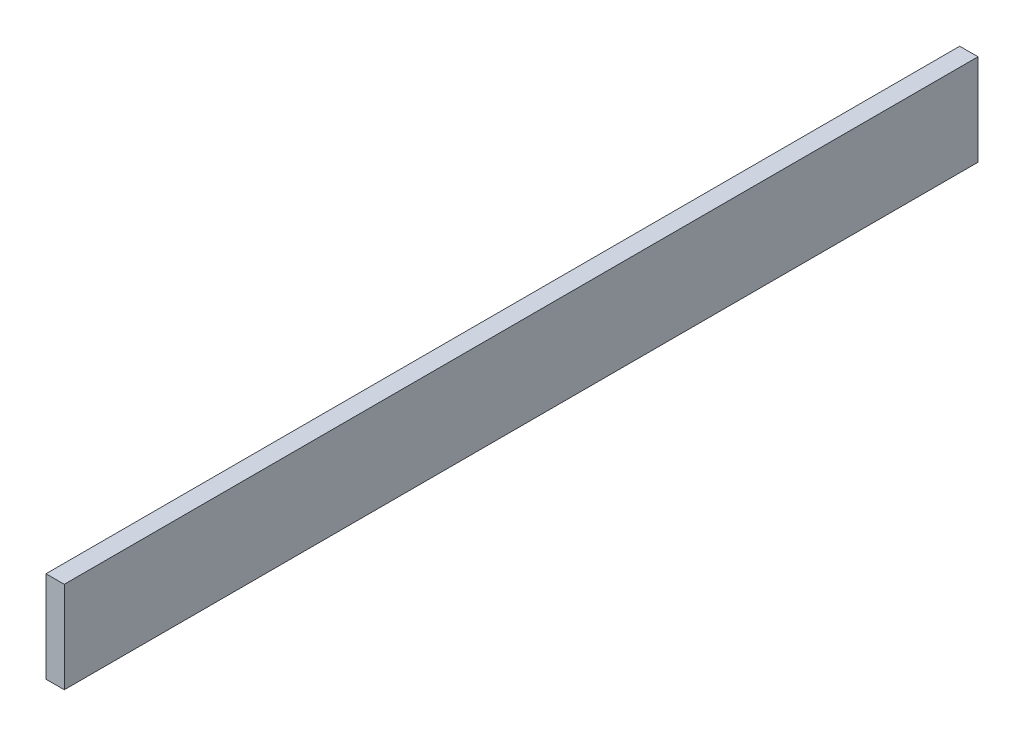
SolidWorks part; units mm, degrees
ref_plane "Front Plane" through (0, 0, 0) normal (0, 0, 1) x (1, 0, 0)
ref_plane "Top Plane" through (0, 0, 0) normal (0, 1, 0) x (1, 0, 0)
ref_plane "Right Plane" through (0, 0, 0) normal (1, 0, 0) x (0, 0, -1)
sketch "Sketch1" plane through (0, 0, 0) normal (0, 0, 1) x (1, 0, 0)
  line L1 (-10, 50) -> (10, 50)
  line L2 (-10, 50) -> (-10, -50)
  line L3 (-10, -50) -> (10, -50)
  line L4 (10, 50) -> (10, -50)
  line L5 (-10, 50) -> (10, -50) construction
  line L6 (-10, -50) -> (10, 50) construction
  point P0 (0, 0)
extrude "Boss-Extrude1" add sketch "Sketch1" along normal blind 1000
